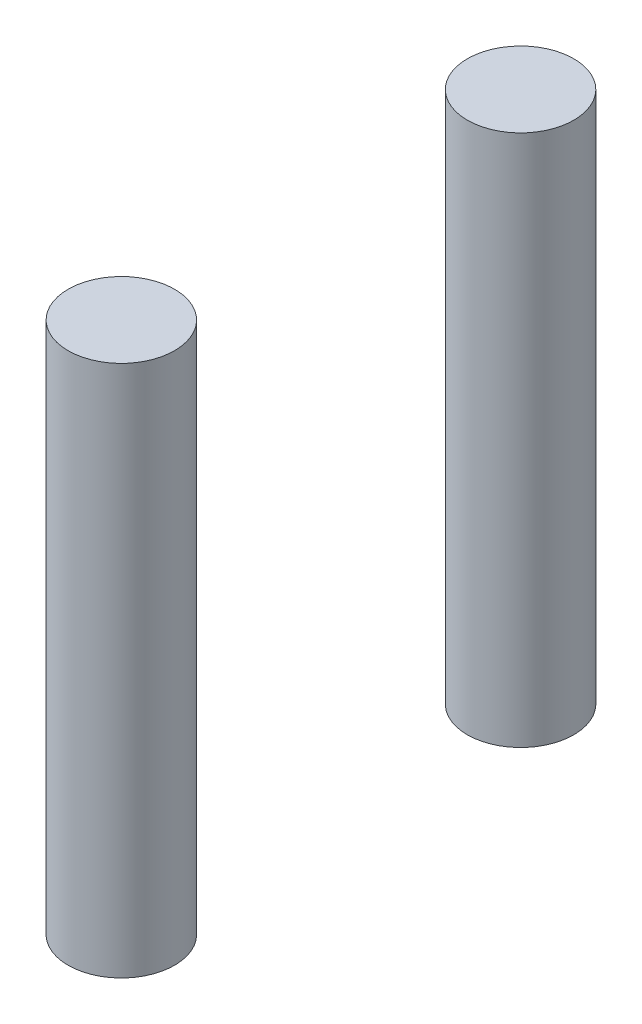
SolidWorks part; units mm, degrees
ref_plane "Спереди" through (0, 0, 0) normal (0, 0, 1) x (1, 0, 0)
ref_plane "Сверху" through (0, 0, 0) normal (0, 1, 0) x (1, 0, 0)
ref_plane "Справа" through (0, 0, 0) normal (1, 0, 0) x (0, 0, -1)
sketch "Эскиз1" plane through (0, 0, 0) normal (0, 1, 0) x (1, 0, 0)
  line L0 (0, 0) -> (0, 3.75) construction
  line L1 (0, 0) -> (0, -3.75) construction
  circle A1 centre (0, -3.75) radius 1
  circle A2 centre (0, 3.75) radius 1
extrude "Бобышка-Вытянуть3" add sketch "Эскиз1" against normal blind 10 from offset 3
